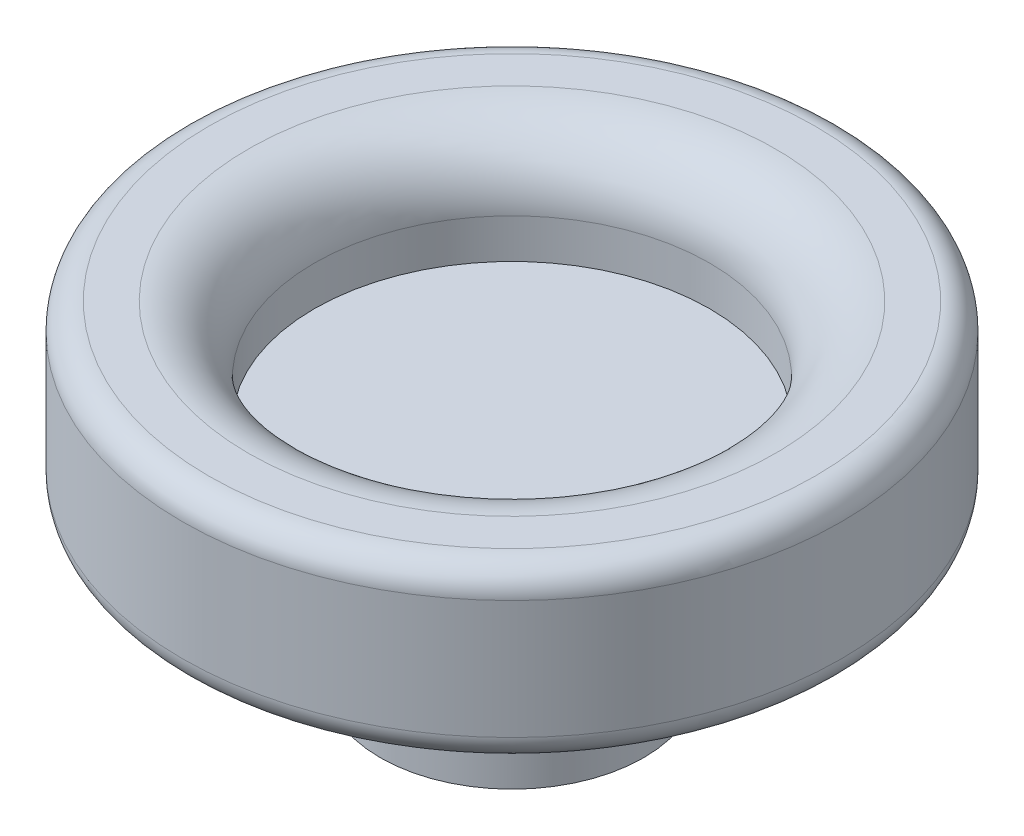
SolidWorks part; units mm, degrees
ref_plane "Front Plane" through (0, 0, 0) normal (0, 0, 1) x (1, 0, 0)
ref_plane "Top Plane" through (0, 0, 0) normal (0, 1, 0) x (1, 0, 0)
ref_plane "Right Plane" through (0, 0, 0) normal (1, 0, 0) x (0, 0, -1)
sketch "Sketch1" plane through (0, 0, 0) normal (0, 1, 0) x (1, 0, 0)
  circle A0 centre (0, 0) radius 7.5
  circle A1 centre (0, 0) radius 10
  dimension "D1" = 15
  dimension "D2" = 20
extrude "Boss-Extrude1" add sketch "Sketch1" along normal blind 15
sketch "Sketch3" plane through (0, 15, 0) normal (0, 1, 0) x (1, 0, 0)
  circle A0 centre (0, 0) radius 25
  dimension "D1" = 50
extrude "Boss-Extrude2" add sketch "Sketch3" along normal blind 10 and the other way blind 3
fillet "Fillet1" radius 2 2 edges at (0, 12, 25) (0, 25, 25)
sketch "Sketch4" plane through (0, 25, 0) normal (0, 1, 0) x (1, 0, 0)
  circle A1 centre (0, 0) radius 15
  dimension "D1" = 30
extrude "Cut-Extrude1" cut sketch "Sketch4" against normal blind 8
fillet "Fillet2" radius 5 1 edges at (0, 25, 15)
